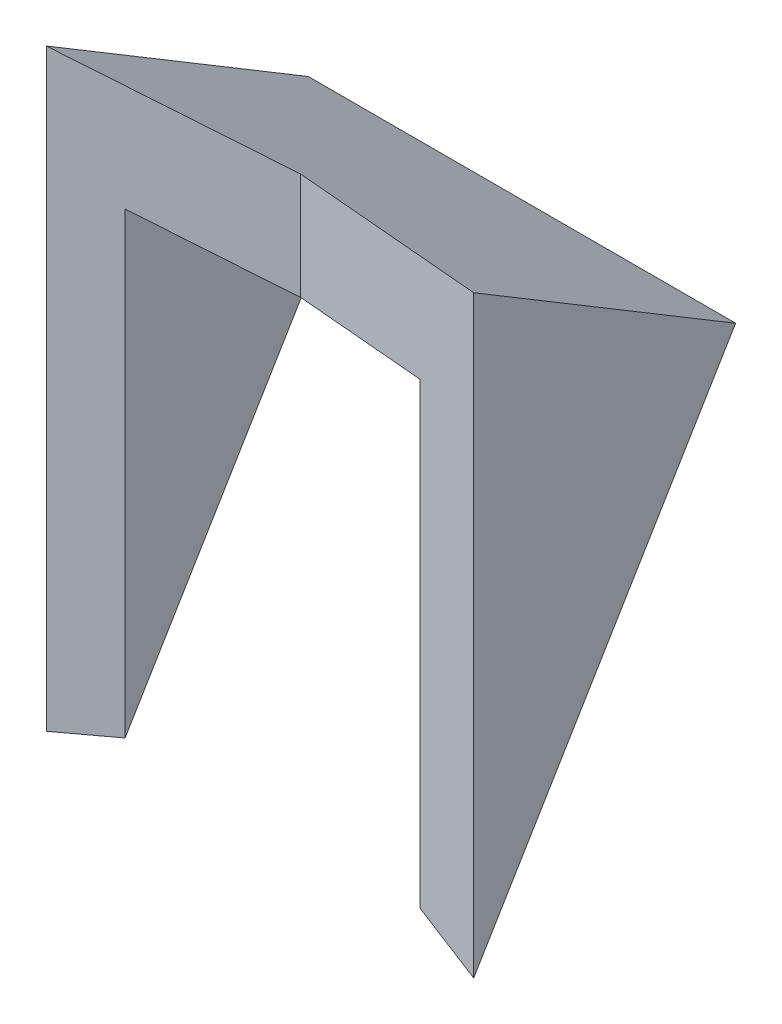
SolidWorks part; units mm, degrees
ref_plane "Спереди" through (0, 0, 0) normal (0, 0, 1) x (1, 0, 0)
ref_plane "Сверху" through (0, 0, 0) normal (0, 1, 0) x (1, 0, 0)
ref_plane "Справа" through (0, 0, 0) normal (1, 0, 0) x (0, 0, -1)
sketch "Эскиз1" plane through (0, 0, 0) normal (1, 0, 0) x (0, 0, -1)
  line L0 (0, 0) -> (-25.7519, 15.4733)
  line L1 (-25.7519, 15.4733) -> (-25.7519, -42.8584)
  line L2 (-25.7519, -42.8584) -> (0, 0)
  line L3 (0, 0) -> (0, -48.7627) construction
  dimension "D1" = 31
  dimension "D2" = 90
  dimension "D3" = 50
extrude "Бобышка-Вытянуть1" add sketch "Эскиз1" along normal blind 42
ref_plane "Плоскость1" through (0, 15.4733, 0) normal (0, 1, 0) x (1, 0, 0)
sketch "Эскиз3" plane through (0, 15.4733, 0) normal (0, 1, 0) x (1, 0, 0)
  line L0 (21, -25.7519) -> (21, 0) construction
  line L1 (42, -25.7519) -> (0, -25.7519) construction
  line L2 (0, -25.7519) -> (21, -21.7519)
  line L3 (21, -21.7519) -> (42, -25.7519)
  line L7 (0, -25.7519) -> (42, -25.7519)
  dimension "D1" = 4
extrude "Вырез-Вытянуть3" cut sketch "Эскиз3" against normal through all contours L3 L7 L2
sketch "Эскиз4" plane through (0, 0, 0) normal (0, -0.515, -0.8572) x (-1, 0, 0)
  line L0 (-35.5, -9) -> (-6.5, -9)
  line L1 (-6.5, -9) -> (-6.5, -47.5961)
  line L2 (0, -50) -> (-21, -42.2336) construction
  line L3 (-6.5, -47.5961) -> (-35.5, -47.5961)
  line L4 (-21, -42.2336) -> (-42, -50) construction
  line L5 (-35.5, -47.5961) -> (-35.5, -9)
  line L6 (-42, 0) -> (0, 0) construction
  line L7 (-42, -50) -> (-42, 0) construction
  line L8 (0, -50) -> (0, 0) construction
  dimension "D1" = 9
  dimension "D2" = 6.5
  dimension "D3" = 6.5
extrude "Вырез-Вытянуть4" cut sketch "Эскиз4" against normal blind 42
